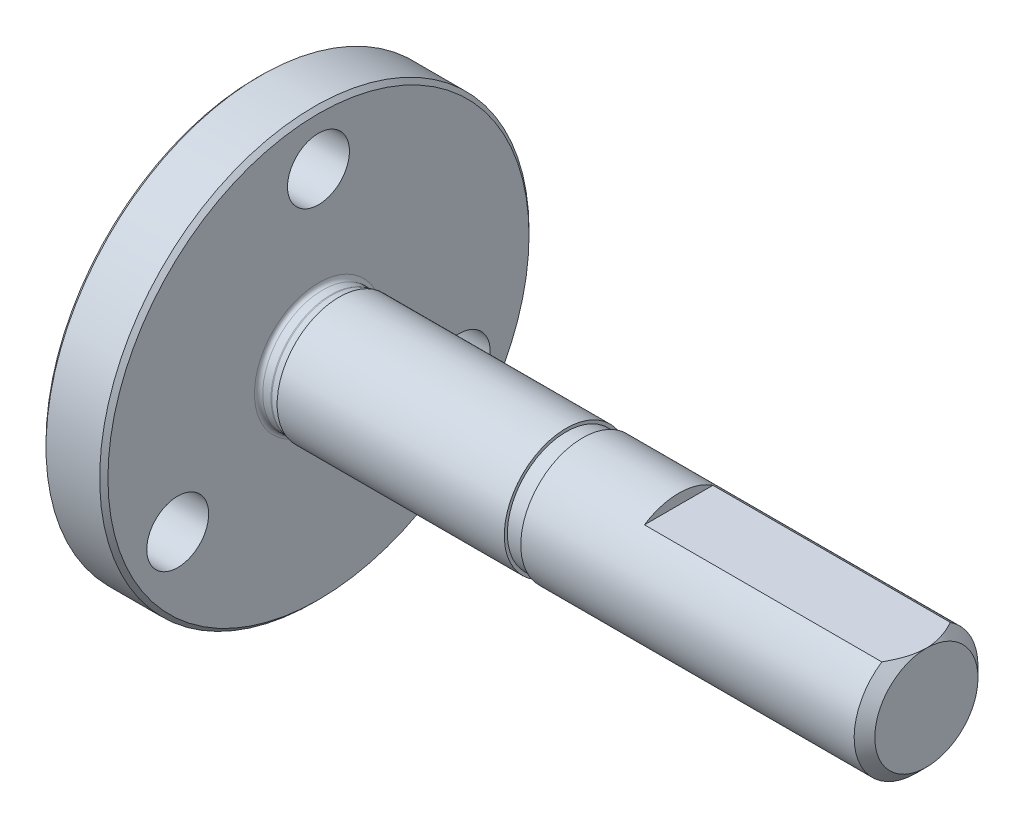
SolidWorks part; units mm, degrees
ref_plane "Face" through (0, 0, 0) normal (0, 0, 1) x (1, 0, 0)
ref_plane "Dessus" through (0, 0, 0) normal (0, 1, 0) x (1, 0, 0)
ref_plane "Droite" through (0, 0, 0) normal (1, 0, 0) x (0, 0, -1)
sketch "Esquisse1" plane through (0, 0, 0) normal (0, 0, 1) x (1, 0, 0)
  line L0 (-3, 10.4) -> (-3, 0)
  line L1 (-3, 0) -> (29.45, 0)
  line L2 (29.45, 0) -> (29.45, 3)
  line L3 (29.45, 3) -> (12.8, 3)
  line L4 (12.8, 3) -> (12.8, 2.85)
  line L5 (12.8, 2.85) -> (12, 2.85)
  line L6 (12, 2.85) -> (12, 3)
  line L7 (12, 3) -> (0.9968, 3)
  line L8 (0.9968, 3) -> (0.6236, 2.9)
  line L9 (0.6236, 2.9) -> (0, 2.9)
  line L10 (0, 2.9) -> (0, 10.4)
  line L11 (0, 10.4) -> (-3, 10.4)
  line L12 (-3, 0) -> (29.45, 0) construction
revolve "Révolution1" add sketch "Esquisse1" angle 360 about L12
hole_wizard "Diamètre du perçage Ø3.0 (3)1" positions "Esquisse3" profile "Esquisse2" hole size "Ø3.0" standard "Ansi Metric"
sketch "Esquisse3" plane through (-3, 0, 0) normal (-1, 0, 0) x (0, 0, 1)
  point P0 (-6.82, -3.9375)
  point P1 (6.82, -3.9375)
  point P2 (0, 7.875)
sketch "Esquisse2" plane through (-3, -3.9375, -6.82) normal (0, 1, 0) x (0, 0, 1)
  line L0 (0, 0) -> (0, 32.45)
  line L1 (0, 32.45) -> (1.5, 32.45)
  line L2 (1.5, 32.45) -> (1.5, 0)
  line L5 (1.5, 0) -> (0, 0)
  line L11 (0, -6.35) -> (0, 107.95) construction
  dimension "Diamètre du perçage jusqu'au prochain" = 3
  dimension "Profondeur du perçage jusqu'au prochain" = 32.45
hole_wizard "Perçage1" positions "Esquisse5" profile "Esquisse4" legacy
sketch "Esquisse5" plane through (-3, 0, 0) normal (-1, 0, 0) x (0, 0, 1)
  point P0 (0, 0)
sketch "Esquisse4" plane through (-3, 0, 0) normal (0, 1, 0) x (0, 0, 1)
  line L0 (0, 0) -> (0, 0.5)
  line L1 (0, 0.5) -> (4.866, 0.5)
  line L2 (4.866, 0.5) -> (5, 0)
  line L3 (5, 0) -> (0, 0)
  line L4 (0, 110) -> (0, -10) construction
  dimension "Diamètre mineur" = 9.7321
  dimension "Profondeur" = 0.5
  dimension "Diamètre majeur" = 10
chamfer "Chanfrein1" distance 0.5 angle 45 1 edges at (29.45, 0, -3)
chamfer "Chanfrein2" distance 0.2 angle 45 2 edges at (0, 0, -10.4) (-3, 0, -10.4)
chamfer "Chanfrein3" distance 0.1732 angle 60 1 edges at (-3, 7.875, 1.5)
chamfer "Chanfrein4" distance 0.3 angle 30 2 edges at (-3, -3.9375, -5.32) (-3, -3.9375, 8.32)
fillet "Congé1" radius 0.2 2 edges at (0, 0, -2.9) (0.6236, 0, -2.9)
sketch "Esquisse6" plane through (29.45, 0, 0) normal (1, 0, 0) x (0, 0, -1)
  line L1 (-4, 2.5) -> (4, 2.5)
  line L2 (-4, 2.5) -> (-4, 4)
  line L3 (-4, 4) -> (4, 4)
  line L4 (4, 2.5) -> (4, 4)
  dimension "D1" = 2.5
extrude "Enlèv. mat.-Extru.1" cut sketch "Esquisse6" against normal blind 12
